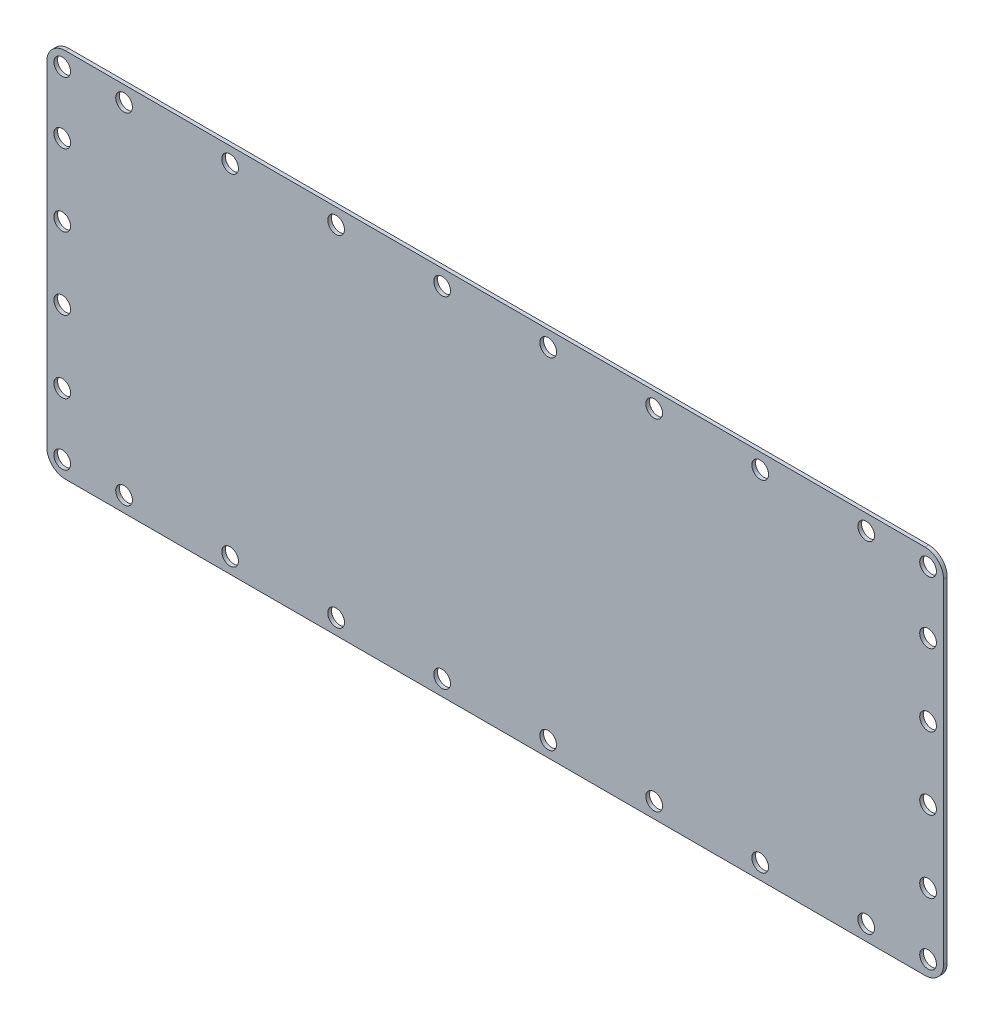
SolidWorks part; units mm, degrees
material "ABS PC"
ref_plane "Front Plane" through (0, 0, 0) normal (0, 0, 1) x (1, 0, 0)
ref_plane "Top Plane" through (0, 0, 0) normal (0, 1, 0) x (1, 0, 0)
ref_plane "Right Plane" through (0, 0, 0) normal (1, 0, 0) x (0, 0, -1)
sketch "Sketch1" plane through (0, 0, 0) normal (0, 0, 1) x (1, 0, 0)
  line L1 (-72.5, 30) -> (72.5, 30)
  line L2 (-72.5, 30) -> (-72.5, -30)
  line L3 (-72.5, -30) -> (72.5, -30)
  line L4 (72.5, 30) -> (72.5, -30)
  line L5 (-72.5, 30) -> (72.5, -30) construction
  line L6 (-72.5, -30) -> (72.5, 30) construction
  dimension "D1" = 145
  dimension "D2" = 60
extrude "Boss-Extrude1" add sketch "Sketch1" along normal blind 0.6
fillet "Fillet1" radius 3 4 edges at (72.5, -30, 0.3) (-72.5, -30, 0.3) (72.5, 30, 0.3) (-72.5, 30, 0.3)
sketch "Sketch2" plane through (0, 0, 0.6) normal (0, 0, 1) x (1, 0, 0)
  line L4 (72.5, -27) -> (72.5, 27) construction
  line L5 (-69.5, -30) -> (69.5, -30) construction
  circle A6 centre (60, -27.5) radius 1.35
  circle A12 centre (42.8571, -27.5) radius 1.35
  circle A14 centre (25.7143, -27.5) radius 1.35
  circle A16 centre (8.5714, -27.5) radius 1.35
  circle A18 centre (-8.5714, -27.5) radius 1.35
  circle A20 centre (-25.7143, -27.5) radius 1.35
  circle A22 centre (-42.8571, -27.5) radius 1.35
  circle A24 centre (-60, -27.5) radius 1.35
  circle A26 centre (-70, -27.5) radius 1.35
  circle A28 centre (-70, -17.5) radius 1.35
  circle A30 centre (-70, -5.8333) radius 1.35
  circle A32 centre (-70, 5.8333) radius 1.35
  circle A34 centre (-70, 17.5) radius 1.35
  circle A36 centre (-70, 27.5) radius 1.35
  circle A38 centre (-60, 27.5) radius 1.35
  circle A40 centre (-42.8571, 27.5) radius 1.35
  circle A42 centre (-25.7143, 27.5) radius 1.35
  circle A44 centre (-8.5714, 27.5) radius 1.35
  circle A46 centre (8.5714, 27.5) radius 1.35
  circle A48 centre (25.7143, 27.5) radius 1.35
  circle A50 centre (42.8571, 27.5) radius 1.35
  circle A52 centre (60, 27.5) radius 1.35
  circle A54 centre (70, -27.5) radius 1.35
  circle A56 centre (70, -17.5) radius 1.35
  circle A58 centre (70, -5.8333) radius 1.35
  circle A60 centre (70, 5.8333) radius 1.35
  circle A62 centre (70, 17.5) radius 1.35
  circle A64 centre (70, 27.5) radius 1.35
  dimension "D1" = 2.7
  dimension "D2" = 2.5
  dimension "D3" = 12.5
  dimension "D4" = 29.6429
  dimension "D5" = 46.7857
  dimension "D6" = 63.9286
  dimension "D7" = 81.0714
  dimension "D8" = 98.2143
  dimension "D9" = 115.3571
  dimension "D10" = 132.5
  dimension "D11" = 142.5
  dimension "D12" = 2.5
  dimension "D13" = 12.5
  dimension "D14" = 24.1667
  dimension "D15" = 35.8333
  dimension "D16" = 47.5
  dimension "D17" = 57.5
extrude "Cut-Extrude1" cut sketch "Sketch2" against normal through all
